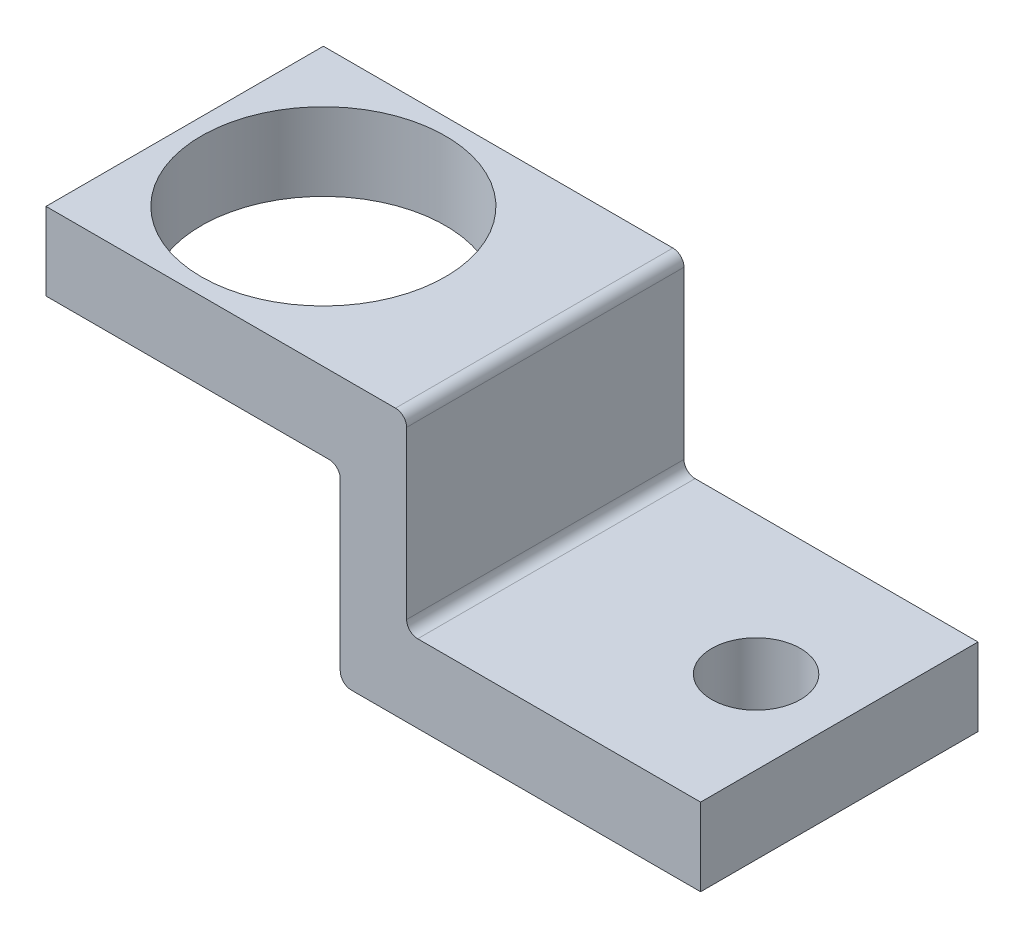
SolidWorks part; units mm, degrees
ref_plane "Front Plane" through (0, 0, 0) normal (0, 0, 1) x (1, 0, 0)
ref_plane "Top Plane" through (0, 0, 0) normal (0, 1, 0) x (1, 0, 0)
ref_plane "Right Plane" through (0, 0, 0) normal (1, 0, 0) x (0, 0, -1)
sketch "Sketch2" plane through (0, 0, 0) normal (0, 0, 1) x (1, 0, 0)
  line L0 (0, 0) -> (0, 7)
  line L1 (0, 7) -> (31.5, 7)
  line L2 (32.5, 6) -> (32.5, -9)
  line L3 (33.5, -10) -> (59.0001, -10)
  line L4 (59.0001, -10) -> (59.0001, -17)
  line L5 (59.0001, -17) -> (27.5201, -17)
  line L6 (26.5201, -16) -> (26.5201, -1)
  line L7 (25.5201, 0) -> (0, 0)
  arc A0 (27.5201, -17) -> (26.5201, -16) centre (27.5201, -16) cw
  arc A1 (33.5, -10) -> (32.5, -9) centre (33.5, -9) cw
  arc A2 (32.5, 6) -> (31.5, 7) centre (31.5, 6) ccw
  arc A3 (26.5201, -1) -> (25.5201, 0) centre (25.5201, -1) ccw
  point P11 (26.5201, -17)
  point P14 (32.5, -10)
  point P17 (32.5, 7)
  point P20 (26.5201, 0)
  dimension "D6" = 1
  dimension "D1" = 7
  dimension "D2" = 32.5
  dimension "D3" = 17
  dimension "D4" = 17
  dimension "D5" = 32.48
extrude "Boss-Extrude1" add sketch "Sketch2" along normal blind 25
sketch "Sketch3" plane through (0, 7, 0) normal (0, 1, 0) x (1, 0, 0)
  line L0 (0, -25) -> (0, 0) construction
  line L1 (0, -12.5) -> (12.5, -12.5)
  circle A0 centre (12.5, -12.5) radius 11
  dimension "D1" = 12.5
extrude "Cut-Extrude1" cut sketch "Sketch3" against normal through all
sketch "Sketch4" plane through (0, -10, 0) normal (0, 1, 0) x (1, 0, 0)
  line L0 (59.0001, -12.5) -> (51.5001, -12.5)
  line L1 (59.0001, -25) -> (59.0001, 0) construction
  circle A0 centre (51.5001, -12.5) radius 4
  dimension "D1" = 7.5
extrude "Cut-Extrude2" cut sketch "Sketch4" against normal through all
